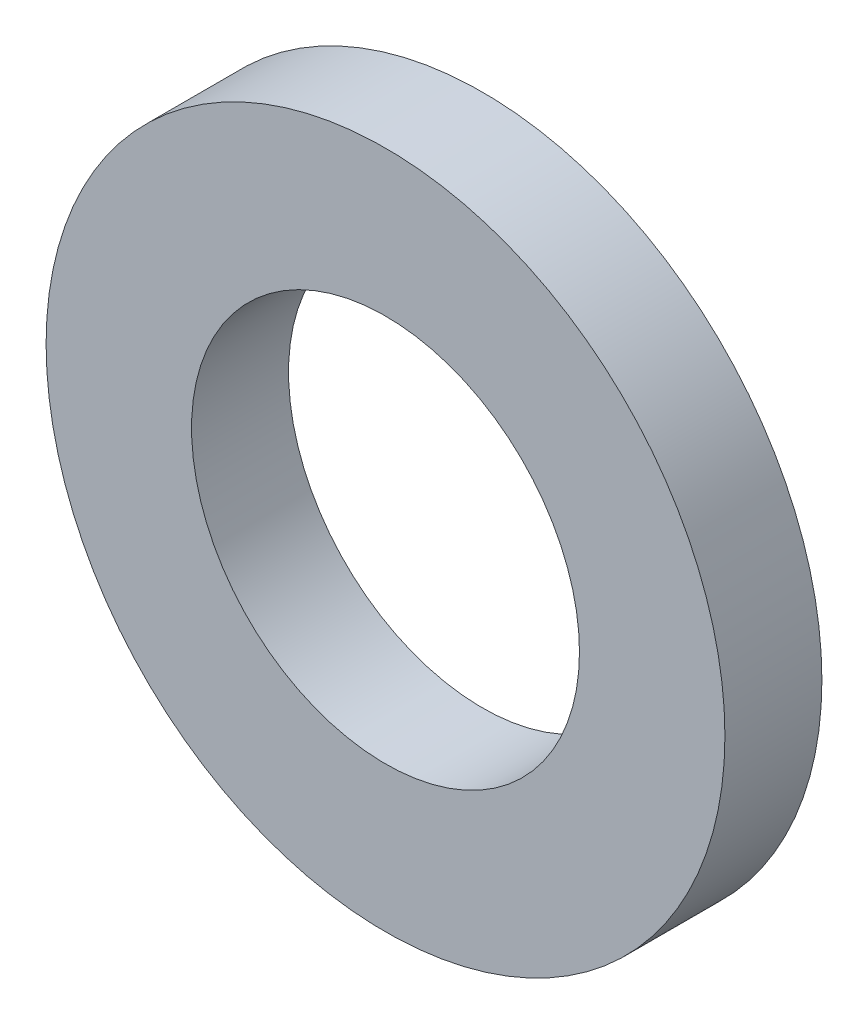
SolidWorks part; units mm, degrees
material "AISI 304"
ref_plane "前视基准面" through (0, 0, 0) normal (0, 0, 1) x (1, 0, 0)
ref_plane "上视基准面" through (0, 0, 0) normal (0, 1, 0) x (1, 0, 0)
ref_plane "右视基准面" through (0, 0, 0) normal (1, 0, 0) x (0, 0, -1)
sketch "草图1" plane through (0, 0, 0) normal (0, 0, 1) x (1, 0, 0)
  circle A0 centre (0, 0) radius 3.5
  circle A1 centre (0, 0) radius 2
  dimension "D1" = 7
  dimension "D2" = 4
extrude "凸台-拉伸1" add sketch "草图1" along normal blind 1
